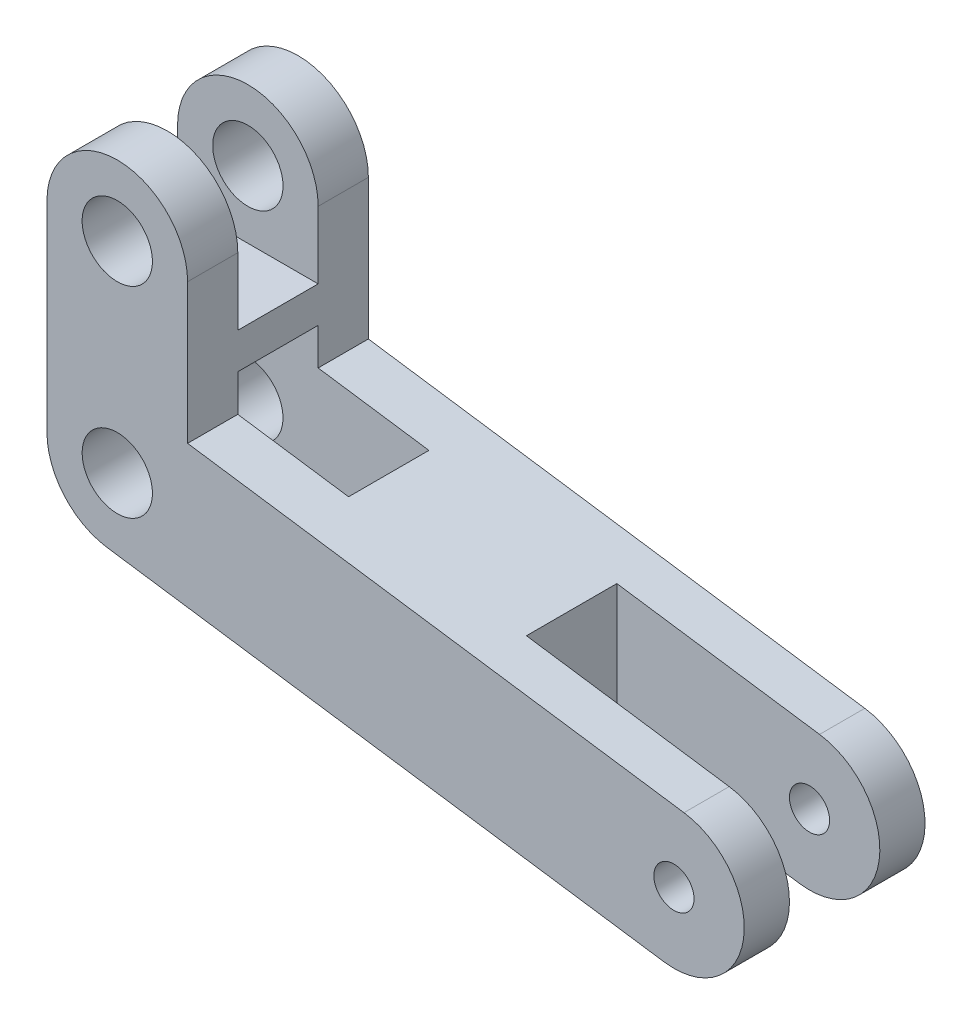
SolidWorks part; units mm, degrees
ref_plane "前视基准面" through (0, 0, 0) normal (0, 0, 1) x (1, 0, 0)
ref_plane "上视基准面" through (0, 0, 0) normal (0, 1, 0) x (1, 0, 0)
ref_plane "右视基准面" through (0, 0, 0) normal (1, 0, 0) x (0, 0, -1)
other "Configuration Table"
sketch "草图1" plane through (0, 0, 0) normal (0, 0, 1) x (1, 0, 0)
  line L0 (0, 10) -> (0, 1.75) construction
  line L1 (27.2128, -7.4641) -> (-0.5, -3.4641)
  line L2 (-3.5, 10) -> (-3.5, 0)
  line L3 (3.5, 10) -> (3.5, 3.0311)
  line L8 (28.2128, -0.5359) -> (3.5, 3.0311)
  line L9 (27.7128, -3) -> (27.7128, -4) construction
  circle A0 centre (0, 0) radius 1.75
  arc A1 (-3.5, 0) -> (-0.5, -3.4641) centre (0, 0) ccw
  arc A2 (3.5, 10) -> (-3.5, 10) centre (0, 10) ccw
  circle A4 centre (0, 10) radius 1.75
  arc A5 (27.2128, -7.4641) -> (28.2128, -0.5359) centre (27.7128, -4) ccw
  circle A6 centre (27.7128, -4) radius 1
  dimension "D1" = 10
  dimension "D2" = 3.5
  dimension "D3" = 7
  dimension "D8" = 2
  dimension "D4" = 28
  dimension "D5" = 4
extrude "凸台-拉伸1" add sketch "草图1" along normal mid plane 9
sketch "草图5" plane through (0, 0, 0) normal (0, 0, 1) x (1, 0, 0)
  line L1 (-5.6997, 16.4699) -> (3.5, 16.4699)
  line L2 (-5.6997, 16.4699) -> (-5.6997, 6.6567)
  line L3 (-5.6997, 6.6567) -> (3.5, 6.6567)
  line L4 (3.5, 16.4699) -> (3.5, 6.6567)
  line L5 (-5.6455, -5.6561) -> (9.0148, -5.6561)
  line L6 (-5.6455, -5.6561) -> (-5.6455, 4.8693)
  line L7 (-5.6455, 4.8693) -> (9.0148, 4.8693)
  line L8 (9.0148, -5.6561) -> (9.0148, 4.8693)
extrude "切除-拉伸3" cut sketch "草图5" against normal mid plane 4
sketch "草图6" plane through (0, 0, 0) normal (0, 0, 1) x (1, 0, 0)
  line L1 (37.3062, -10) -> (18.1194, -10)
  line L2 (37.3062, -10) -> (37.3062, 2)
  line L3 (37.3062, 2) -> (18.1194, 2)
  line L4 (18.1194, -10) -> (18.1194, 2)
  line L5 (37.3062, -10) -> (18.1194, 2) construction
  line L6 (37.3062, 2) -> (18.1194, -10) construction
  point P0 (27.7128, -4)
  dimension "D1" = 6
extrude "切除-拉伸4" cut sketch "草图6" against normal mid plane 4.5
